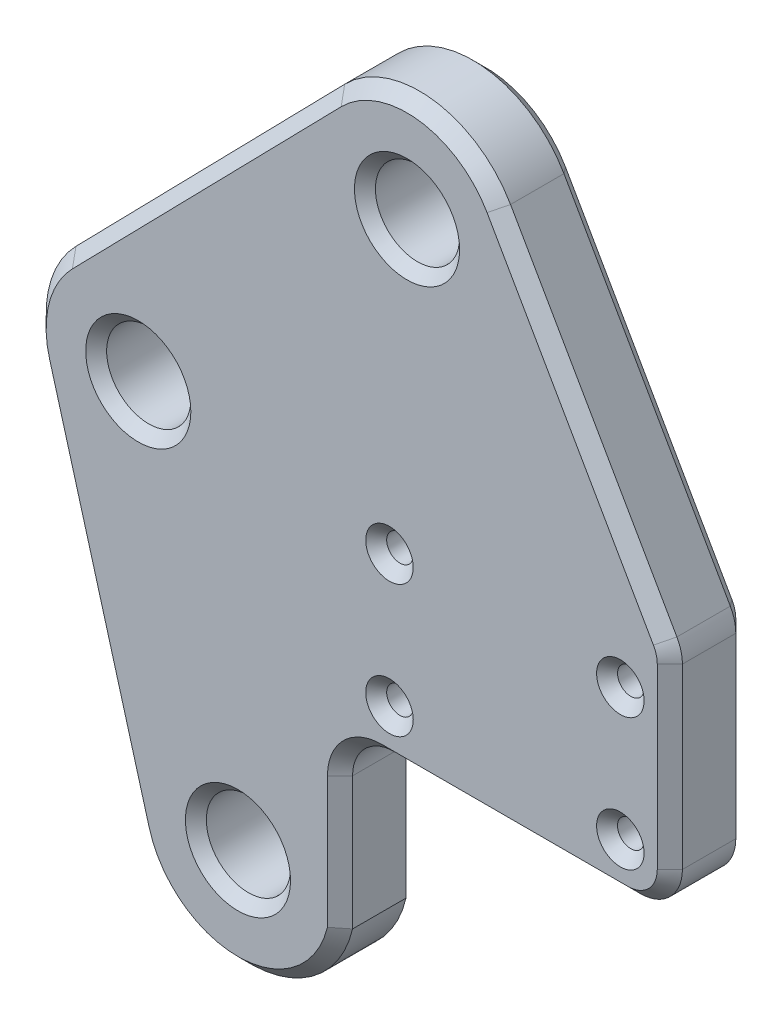
SolidWorks part; units mm, degrees
material "PET"
ref_plane "Front Plane" through (0, 0, 0) normal (0, 0, 1) x (1, 0, 0)
ref_plane "Top Plane" through (0, 0, 0) normal (0, 1, 0) x (1, 0, 0)
ref_plane "Right Plane" through (0, 0, 0) normal (1, 0, 0) x (0, 0, -1)
sketch "Sketch2" plane through (0, 0, 49.9814) normal (0, 0, 1) x (1, 0, 0)
  line L0 (-88.5343, -220.6839) -> (-74.5343, -212.6839) construction
  line L1 (-71.5343, -209.6839) -> (-81.956, -191.4306)
  line L2 (-71.5343, -223.6839) -> (-91.5343, -223.6839)
  line L3 (-71.5343, -223.6839) -> (-71.5343, -209.6839)
  line L4 (-71.5343, -209.6839) -> (-91.5343, -209.6839)
  line L5 (-91.5343, -223.6839) -> (-91.5343, -209.6839)
  line L6 (-71.5343, -223.6839) -> (-91.5343, -209.6839) construction
  line L7 (-71.5343, -209.6839) -> (-91.5343, -223.6839) construction
  line L8 (-92.0102, -190.1391) -> (-108.3079, -206.8031)
  line L9 (-109.8832, -212.9546) -> (-103.8379, -234.5533)
  line L10 (-91.5343, -223.6839) -> (-91.5343, -234.2645)
  circle A0 centre (-87.4705, -194.5791) radius 6.35
  circle A1 centre (-103.7682, -211.243) radius 6.35
  arc A2 (-91.5343, -231.419) -> (-91.5343, -234.2645) centre (-97.7229, -232.8418) ccw
  point P4 (-81.5343, -216.6839)
  point P19 (0, 0)
  dimension "D1" = 12.7
extrude "Boss-Extrude1" add sketch "Sketch2" along normal blind 4.7625
hole_wizard "#10 Clearance Hole1" positions "Sketch6" profile "Sketch7" hole size "#10" standard "ANSI Inch" end condition through all
sketch "Sketch6" plane through (0, 0, 54.7439) normal (0, 0, 1) x (1, 0, 0)
  point P0 (-97.7229, -232.8418)
  point P3 (-87.4705, -194.5791)
  point P6 (-103.7682, -211.243)
sketch "Sketch7" plane through (-97.7229, -232.8418, 54.7439) normal (1, 0, 0) x (0, -1, 0)
  line L0 (0, 0) -> (0, 4.7625)
  line L1 (0, 4.7625) -> (3.1877, 4.7625)
  line L2 (2.5527, 4.1275) -> (2.5527, 0.635)
  line L3 (2.5527, 0.635) -> (3.1877, 0)
  line L5 (3.1877, 0) -> (0, 0)
  line L6 (-2.5527, 0.635) -> (-3.1877, 0) construction
  line L7 (3.1877, 4.7625) -> (2.5527, 4.1275)
  line L8 (-3.1877, 4.7625) -> (-2.5527, 4.1275) construction
  line L11 (0, -6.35) -> (0, 107.95) construction
  dimension "Thru Hole Dia." = 5.1054
  dimension "Thru Hole Depth" = 4.7625
  dimension "Near C'Sink Dia." = 6.3754
  dimension "Near C'Sink Angle" = 90
  dimension "Far C'Sink Dia." = 6.3754
  dimension "Far C'Sink Angle" = 90
fillet "Fillet1" radius 2.54 3 edges at (-71.5343, -209.6839, 52.3626) (-91.5343, -223.6839, 52.3626) (-71.5343, -223.6839, 52.3626)
hole_wizard "#52 (0.0635) Diameter Hole1" positions "Sketch8" profile "Sketch9" hole size "#52" standard "ANSI Inch" end condition through all
sketch "Sketch8" plane through (0, 0, 54.7439) normal (0, 0, 1) x (1, 0, 0)
  circle A0 centre (-88.5343, -212.6839) radius 1.25 construction
  circle A1 centre (-88.5343, -220.6839) radius 1.25 construction
  circle A2 centre (-74.5343, -212.6839) radius 1.25 construction
  circle A3 centre (-74.5343, -220.6839) radius 1.25 construction
  point P0 (-88.5343, -212.6839)
  point P2 (-74.5343, -212.6839)
  point P4 (-74.5343, -220.6839)
  point P6 (-88.5343, -220.6839)
  point P9 (0, 0)
  point P12 (0, 0)
  point P15 (0, 0)
  point P18 (0, 0)
sketch "Sketch9" plane through (-88.5343, -212.6839, 54.7439) normal (1, 0, 0) x (0, -1, 0)
  line L0 (0, 0) -> (0, 4.7625)
  line L1 (0, 4.7625) -> (1.4414, 4.7625)
  line L2 (0.8064, 4.1275) -> (0.8064, 0.635)
  line L3 (0.8064, 0.635) -> (1.4414, 0)
  line L5 (1.4414, 0) -> (0, 0)
  line L6 (-0.8064, 0.635) -> (-1.4414, 0) construction
  line L7 (1.4414, 4.7625) -> (0.8064, 4.1275)
  line L8 (-1.4415, 4.7625) -> (-0.8064, 4.1275) construction
  line L11 (0, -6.35) -> (0, 107.95) construction
  dimension "Thru Hole Dia." = 1.6129
  dimension "Thru Hole Depth" = 4.7625
  dimension "Near C'Sink Dia." = 2.8829
  dimension "Near C'Sink Angle" = 90
  dimension "Far C'Sink Dia." = 2.8829
  dimension "Far C'Sink Angle" = 90
chamfer "Chamfer4" distance 0.762 angle 45 24 edges at (-97.5739, -239.19, 49.9814) (-97.5739, -239.19, 54.7439) (-106.8606, -223.754, 49.9814) (-106.8606, -223.754, 54.7439) (-109.9197, -209.6678, 49.9814) (-109.9197, -209.6678, 54.7439) (-91.5343, -230.2442, 49.9814) (-91.5343, -230.2442, 54.7439) (-100.1591, -198.4711, 49.9814) (-100.1591, -198.4711, 54.7439) (-90.7904, -224.4279, 54.7439) (-90.7904, -224.4279, 49.9814) (-86.6614, -188.2809, 49.9814) (-86.6614, -188.2809, 54.7439) (-81.5343, -223.6839, 54.7439) (-81.5343, -223.6839, 49.9814) (-76.9123, -200.2646, 54.7439) (-76.9123, -200.2646, 49.9814) (-72.2783, -222.94, 54.7439) (-72.2783, -222.94, 49.9814) (-71.6193, -209.7065, 54.7439) (-71.6193, -209.7065, 49.9814) (-71.5343, -215.7509, 49.9814) (-71.5343, -215.7509, 54.7439)
